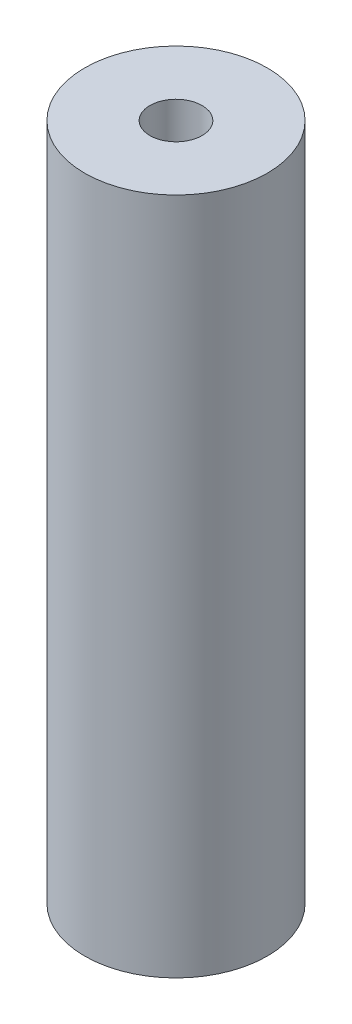
SolidWorks part; units mm, degrees
ref_plane "Front Plane" through (0, 0, 0) normal (0, 0, 1) x (1, 0, 0)
ref_plane "Top Plane" through (0, 0, 0) normal (0, 1, 0) x (1, 0, 0)
ref_plane "Right Plane" through (0, 0, 0) normal (1, 0, 0) x (0, 0, -1)
sketch "Sketch1" plane through (0, 0, 0) normal (0, 1, 0) x (1, 0, 0)
  circle A0 centre (0, 0) radius 8.75
extrude "Boss-Extrude1" add sketch "Sketch1" along normal blind 65
sketch "Sketch2" plane through (0, 0, 0) normal (0, 1, 0) x (1, 0, 0)
  circle A0 centre (0, 0) radius 2.5
extrude "Cut-Extrude1" cut sketch "Sketch2" along normal blind 131
